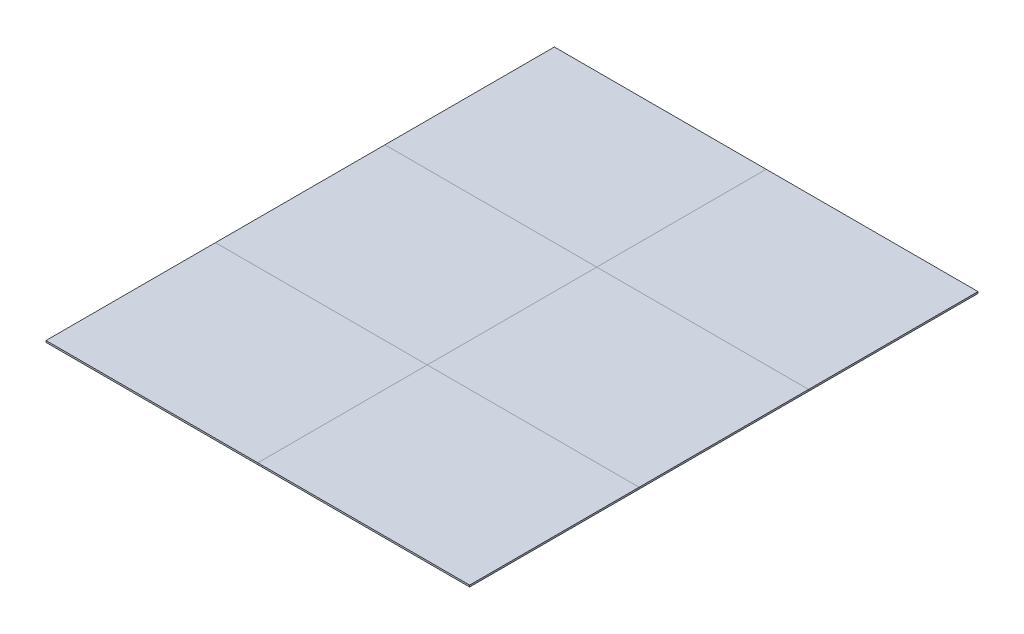
SolidWorks part; units mm, degrees
ref_plane "前视基准面" through (0, 0, 0) normal (0, 0, 1) x (1, 0, 0)
ref_plane "上视基准面" through (0, 0, 0) normal (0, 1, 0) x (1, 0, 0)
ref_plane "右视基准面" through (0, 0, 0) normal (1, 0, 0) x (0, 0, -1)
sketch "草图1" plane through (0, 0, 0) normal (0, 1, 0) x (1, 0, 0)
  line L1 (0, 0) -> (2500, 0)
  line L2 (0, 0) -> (0, 2000)
  line L3 (0, 2000) -> (2500, 2000)
  line L4 (2500, 0) -> (2500, 2000)
  dimension "D1" = 2500
  dimension "D2" = 2000
extrude "凸台-拉伸1" add sketch "草图1" against normal blind 20
pattern_linear "阵列(线性)2" count 3 spacing 2000 along (0, 0, -1) count 2 spacing 2500 along (1, 0, 0) of bodies 106
